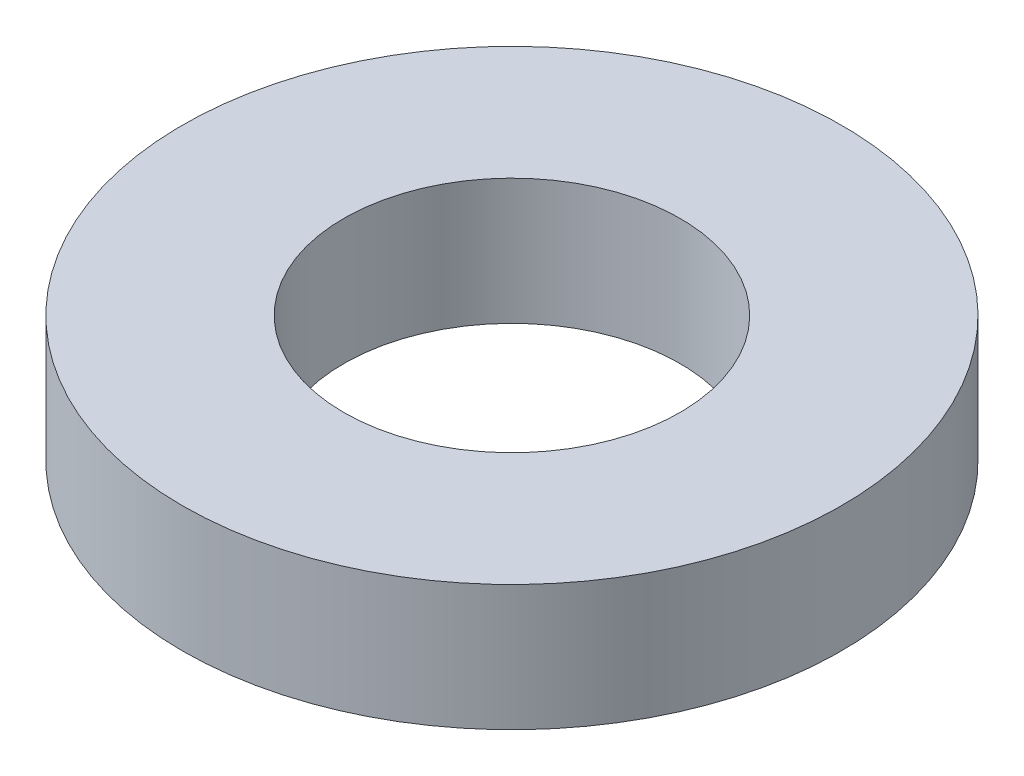
SolidWorks part; units mm, degrees
ref_plane "Front Plane" through (0, 0, 0) normal (0, 0, 1) x (1, 0, 0)
ref_plane "Top Plane" through (0, 0, 0) normal (0, 1, 0) x (1, 0, 0)
ref_plane "Right Plane" through (0, 0, 0) normal (1, 0, 0) x (0, 0, -1)
sketch "Sketch1" plane through (0, 0, 0) normal (0, 1, 0) x (1, 0, 0)
  circle A0 centre (0, 0) radius 2.5
  circle A1 centre (0, 0) radius 4.9
  dimension "D1" = 5
  dimension "D2" = 2.4
extrude "Boss-Extrude1" add sketch "Sketch1" along normal blind 1.87
